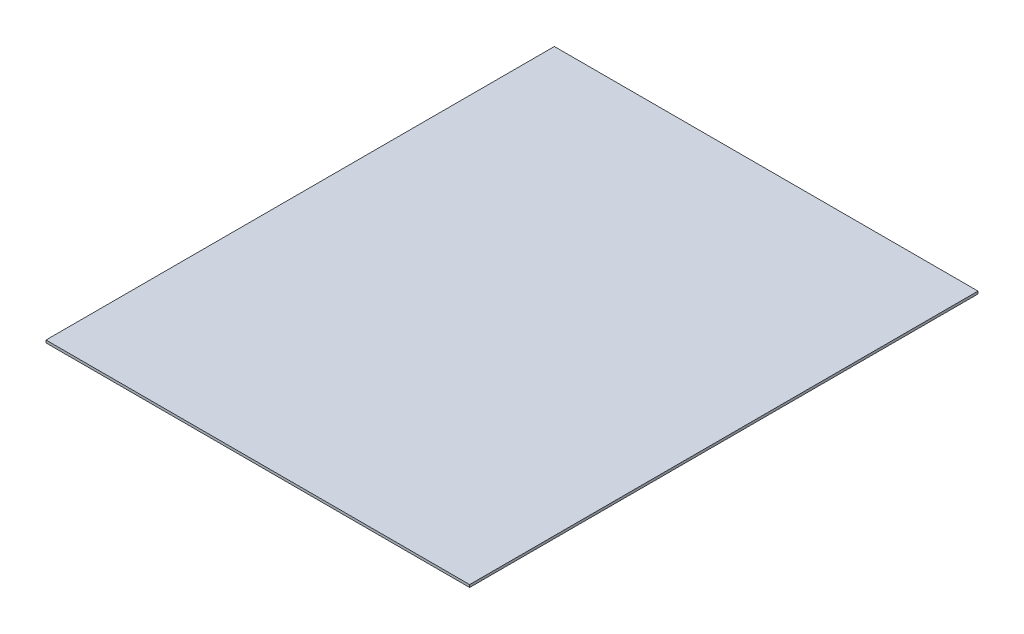
SolidWorks part; units mm, degrees
ref_plane "Front Plane" through (0, 0, 0) normal (0, 0, 1) x (1, 0, 0)
ref_plane "Top Plane" through (0, 0, 0) normal (0, 1, 0) x (1, 0, 0)
ref_plane "Right Plane" through (0, 0, 0) normal (1, 0, 0) x (0, 0, -1)
sketch "Sketch2" plane through (0, 0, 0) normal (0, 1, 0) x (1, 0, 0)
  line L1 (-20.3333, 15.5833) -> (479.6667, 15.5833)
  line L2 (-20.3333, 15.5833) -> (-20.3333, -584.4167)
  line L3 (-20.3333, -584.4167) -> (479.6667, -584.4167)
  line L4 (479.6667, 15.5833) -> (479.6667, -584.4167)
  dimension "D1" = 500
  dimension "D2" = 600
extrude "Boss-Extrude1" add sketch "Sketch2" along normal blind 3
